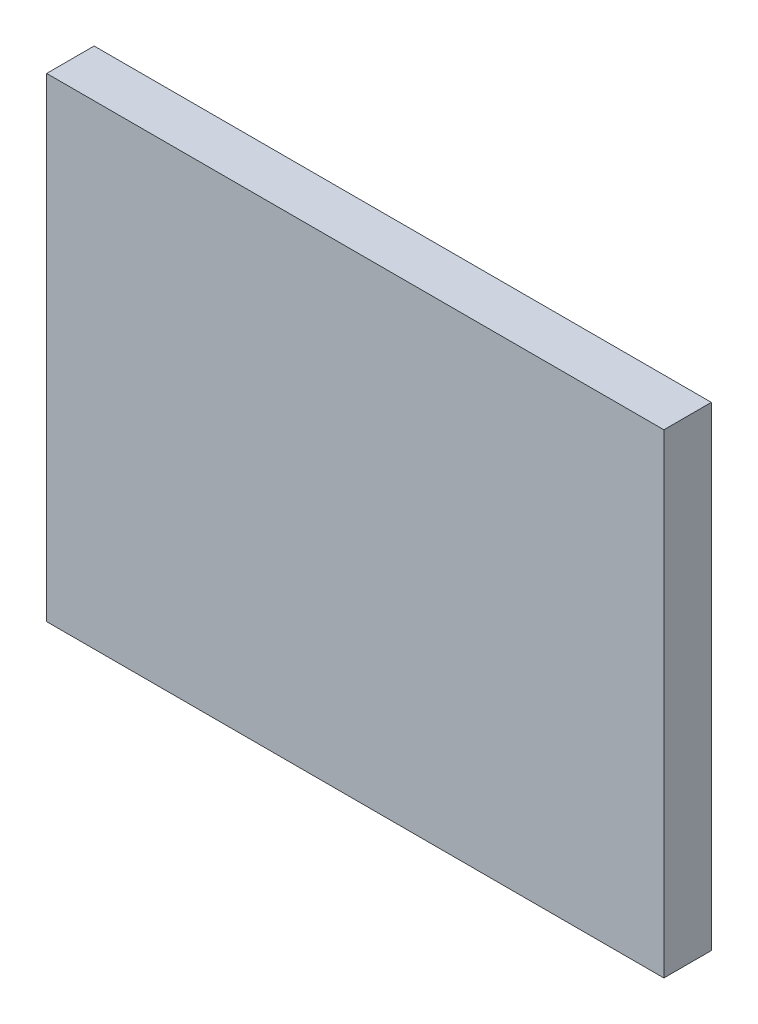
SolidWorks part; units mm, degrees
ref_plane "Plan de face" through (0, 0, 0) normal (0, 0, 1) x (1, 0, 0)
ref_plane "Plan de dessus" through (0, 0, 0) normal (0, 1, 0) x (1, 0, 0)
ref_plane "Plan de droite" through (0, 0, 0) normal (1, 0, 0) x (0, 0, -1)
sketch "Esquisse1" plane through (0, 0, 0) normal (0, 0, 1) x (1, 0, 0)
  line L0 (-88.4513, 0) -> (41.5487, 0)
  line L1 (41.5487, 0) -> (41.5487, 100)
  line L2 (41.5487, 100) -> (-88.4513, 100)
  line L3 (-88.4513, 100) -> (-88.4513, 0)
  dimension "D1" = 130
  dimension "D2" = 100
extrude "Boss.-Extru.1" add sketch "Esquisse1" along normal blind 10
